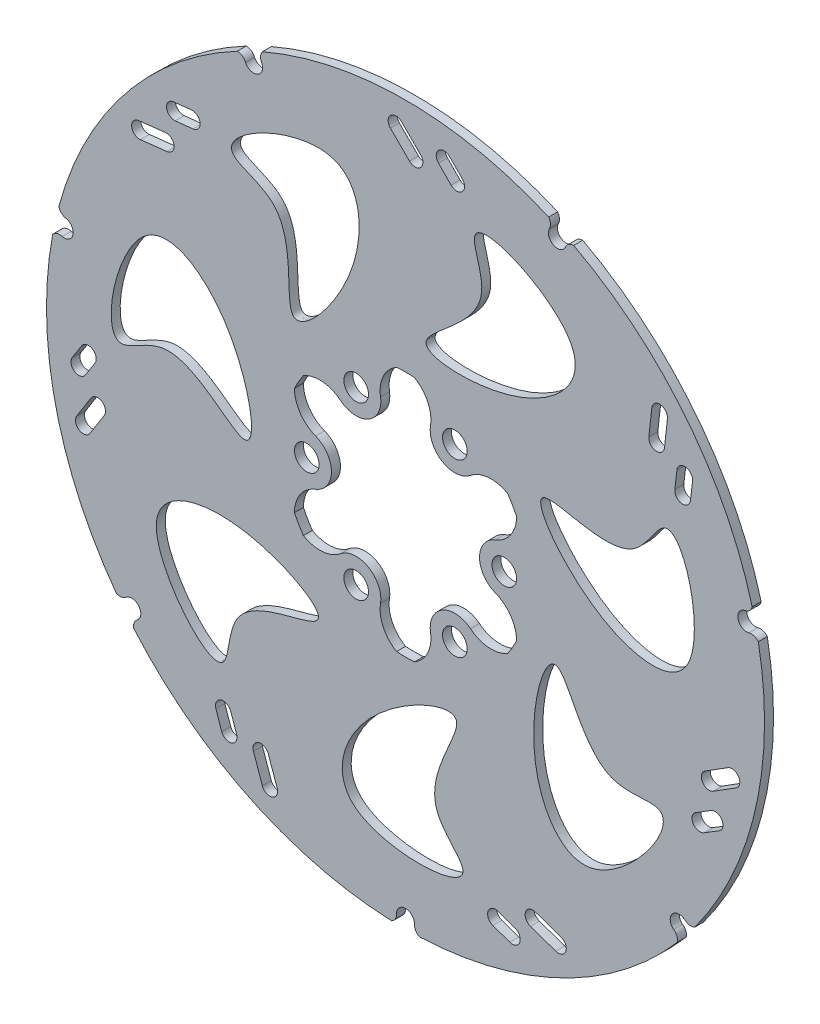
SolidWorks part; units mm, degrees
ref_plane "Płaszczyzna przednia" through (0, 0, 0) normal (0, 0, 1) x (1, 0, 0)
ref_plane "Płaszczyzna górna" through (0, 0, 0) normal (0, 1, 0) x (1, 0, 0)
ref_plane "Płaszczyzna prawa" through (0, 0, 0) normal (1, 0, 0) x (0, 0, -1)
sketch "Szkic1" plane through (0, 0, 0) normal (0, 0, 1) x (1, 0, 0)
  line L0 (0, 100.2963) -> (0, -100.5622) construction
  line L1 (96.5218, 0) -> (-95.8606, 0) construction
  line L2 (0, 72) -> (-5.2968, 77.2968) construction
  line L3 (0, 72) -> (7.8433, 64.1567) construction
  line L4 (-2.1213, 74.1213) -> (2.1213, 69.8787) construction
  line L5 (-0.8839, 75.3588) -> (3.3588, 71.1161)
  line L6 (-3.3588, 72.8839) -> (0.8839, 68.6412)
  line L7 (10, 71.3022) -> (13.4645, 67.8377) construction
  line L8 (10, 71.3022) -> (6.4186, 74.9311) construction
  line L9 (8.5951, 72.7257) -> (11.4049, 69.8787) construction
  line L10 (9.8407, 73.9549) -> (12.6504, 71.1079)
  line L11 (7.3496, 71.4964) -> (10.1593, 68.6494)
  line L12 (54.8888, 48.0683) -> (54.217, 42.1061)
  line L13 (14.2339, 69.8787) -> (-2.5812, 69.8787) construction
  line L14 (58.3668, 47.6765) -> (57.695, 41.7142)
  line L15 (60.4805, 38.8312) -> (60.0065, 34.8593)
  line L16 (63.9559, 38.4164) -> (63.4818, 34.4446)
  line L17 (56.6278, 47.8724) -> (55.956, 41.9101) construction
  line L18 (62.2182, 38.6238) -> (61.7442, 34.652) construction
  line L19 (71.8039, -12.9436) -> (66.7236, -16.1358)
  line L20 (73.666, -15.9072) -> (68.5857, -19.0994)
  line L21 (68.0684, -23.0747) -> (64.6676, -25.1805)
  line L22 (69.911, -26.0505) -> (66.5101, -28.1563)
  line L23 (72.735, -14.4254) -> (67.6546, -17.6176) construction
  line L24 (68.9897, -24.5626) -> (65.5889, -26.6684) construction
  line L25 (34.6493, -64.2088) -> (28.986, -62.2271)
  line L26 (33.4933, -67.5124) -> (27.83, -65.5307)
  line L27 (24.3994, -67.6049) -> (20.6326, -66.2589)
  line L28 (23.2217, -70.9008) -> (19.4549, -69.5549)
  line L29 (34.0713, -65.8606) -> (28.408, -63.8789) construction
  line L30 (23.8105, -69.2528) -> (20.0438, -67.9069) construction
  line L31 (-28.597, -67.1234) -> (-30.5787, -61.4601)
  line L32 (-31.9006, -68.2794) -> (-33.8823, -62.6161)
  line L33 (-37.6429, -61.2272) -> (-38.9391, -57.443)
  line L34 (-40.954, -62.3614) -> (-42.2502, -58.5772)
  line L35 (-30.2488, -67.7014) -> (-32.2305, -62.0381) construction
  line L36 (-39.2984, -61.7943) -> (-40.5947, -58.0101) construction
  line L37 (-70.3091, -19.4927) -> (-67.1169, -14.4124)
  line L38 (-73.2727, -17.6306) -> (-70.0805, -12.5503)
  line L39 (-71.3393, -8.7441) -> (-69.1889, -5.3713)
  line L40 (-74.2905, -6.8626) -> (-72.1401, -3.4897)
  line L41 (-71.7909, -18.5617) -> (-68.5987, -13.4813) construction
  line L42 (-72.8149, -7.8034) -> (-70.6645, -4.4305) construction
  line L43 (-59.0771, 42.8164) -> (-53.1148, 43.4882)
  line L44 (-59.4689, 46.2944) -> (-53.5067, 46.9662)
  line L45 (-51.3158, 50.3234) -> (-47.338, 50.7451)
  line L46 (-51.6847, 53.8039) -> (-47.707, 54.2256)
  line L47 (-59.273, 44.5554) -> (-53.3107, 45.2272) construction
  line L48 (-51.5002, 52.0637) -> (-47.5225, 52.4853) construction
  line L49 (0, 0) -> (0.8839, 68.6412) construction
  line L50 (-7.2215, -78) -> (6.4186, -78) construction
  line L51 (0, 0) -> (0, -78) construction
  line L52 (24.75, 11.987) -> (24.75, 17.3566) construction
  line L53 (24.75, -11.987) -> (24.75, -17.6176) construction
  line L54 (10.5123, -30.9016) -> (-11.2813, -62.0261) construction
  circle A0 centre (0, 0) radius 80
  circle A1 centre (0, 0) radius 22 construction
  circle A2 centre (0, 0) radius 72 construction
  circle A3 centre (0, 0) radius 16.5
  arc A4 (-0.8839, 75.3588) -> (-3.3588, 72.8839) centre (-2.1213, 74.1213) ccw
  arc A5 (0.8839, 68.6412) -> (3.3588, 71.1161) centre (2.1213, 69.8787) ccw
  arc A6 (9.8407, 73.9549) -> (7.3496, 71.4964) centre (8.5951, 72.7257) ccw
  arc A7 (10.1593, 68.6494) -> (12.6504, 71.1079) centre (11.4049, 69.8787) ccw
  arc A8 (58.3668, 47.6765) -> (54.8888, 48.0683) centre (56.6278, 47.8724) ccw
  arc A9 (54.217, 42.1061) -> (57.695, 41.7142) centre (55.956, 41.9101) ccw
  arc A10 (63.9559, 38.4164) -> (60.4805, 38.8312) centre (62.2182, 38.6238) ccw
  arc A11 (60.0065, 34.8593) -> (63.4818, 34.4446) centre (61.7442, 34.652) ccw
  arc A12 (73.666, -15.9072) -> (71.8039, -12.9436) centre (72.735, -14.4254) ccw
  arc A13 (66.7236, -16.1358) -> (68.5857, -19.0994) centre (67.6546, -17.6176) ccw
  arc A14 (69.911, -26.0505) -> (68.0684, -23.0747) centre (68.9897, -24.5626) ccw
  arc A15 (64.6676, -25.1805) -> (66.5101, -28.1563) centre (65.5889, -26.6684) ccw
  arc A16 (33.4933, -67.5124) -> (34.6493, -64.2088) centre (34.0713, -65.8606) ccw
  arc A17 (28.986, -62.2271) -> (27.83, -65.5307) centre (28.408, -63.8789) ccw
  arc A18 (23.2217, -70.9008) -> (24.3994, -67.6049) centre (23.8105, -69.2528) ccw
  arc A19 (20.6326, -66.2589) -> (19.4549, -69.5549) centre (20.0438, -67.9069) ccw
  arc A20 (-31.9006, -68.2794) -> (-28.597, -67.1234) centre (-30.2488, -67.7014) ccw
  arc A21 (-30.5787, -61.4601) -> (-33.8823, -62.6161) centre (-32.2305, -62.0381) ccw
  arc A22 (-40.954, -62.3614) -> (-37.6429, -61.2272) centre (-39.2984, -61.7943) ccw
  arc A23 (-38.9391, -57.443) -> (-42.2502, -58.5772) centre (-40.5947, -58.0101) ccw
  arc A24 (-73.2727, -17.6306) -> (-70.3091, -19.4927) centre (-71.7909, -18.5617) ccw
  arc A25 (-67.1169, -14.4124) -> (-70.0805, -12.5503) centre (-68.5987, -13.4813) ccw
  arc A26 (-74.2905, -6.8626) -> (-71.3393, -8.7441) centre (-72.8149, -7.8034) ccw
  arc A27 (-69.1889, -5.3713) -> (-72.1401, -3.4897) centre (-70.6645, -4.4305) ccw
  arc A28 (-59.4689, 46.2944) -> (-59.0771, 42.8164) centre (-59.273, 44.5554) ccw
  arc A29 (-53.1148, 43.4882) -> (-53.5067, 46.9662) centre (-53.3107, 45.2272) ccw
  arc A30 (-51.6847, 53.8039) -> (-51.3158, 50.3234) centre (-51.5002, 52.0637) ccw
  arc A31 (-47.338, 50.7451) -> (-47.707, 54.2256) centre (-47.5225, 52.4853) ccw
  circle A32 centre (0, -78) radius 2 construction
  arc A33 (-2, -78) -> (2, -78) centre (0, -78) cw
  arc A34 (2, -78) -> (3.0983, -79.94) centre (3.9942, -78.1519) ccw
  arc A35 (-2, -78) -> (-3.0983, -79.94) centre (-3.9942, -78.1519) cw
  arc A36 (-59.7359, -50.1959) -> (-60.5679, -52.2641) centre (-58.6113, -51.8497) ccw
  arc A37 (-62.2298, -47.0685) -> (-59.7359, -50.1959) centre (-60.9829, -48.6322) cw
  arc A38 (-62.2298, -47.0685) -> (-64.4313, -47.4195) centre (-63.592, -45.6041) cw
  arc A39 (-76.4894, 15.4068) -> (-78.6251, 14.7677) centre (-77.0813, 13.4964) ccw
  arc A40 (-75.5993, 19.3065) -> (-76.4894, 15.4068) centre (-76.0444, 17.3566) cw
  arc A41 (-75.5993, 19.3065) -> (-77.2463, 20.8089) centre (-75.3037, 21.2845) cw
  arc A42 (-35.6449, 69.4078) -> (-37.4761, 70.6792) centre (-37.5075, 68.6794) ccw
  arc A43 (-32.041, 71.1433) -> (-35.6449, 69.4078) centre (-33.8429, 70.2756) cw
  arc A44 (-32.041, 71.1433) -> (-31.8932, 73.3677) centre (-30.3102, 72.1455) cw
  arc A45 (32.041, 71.1433) -> (31.8932, 73.3677) centre (30.3102, 72.1455) ccw
  arc A46 (35.6449, 69.4078) -> (32.041, 71.1433) centre (33.8429, 70.2756) cw
  arc A47 (35.6449, 69.4078) -> (37.4761, 70.6792) centre (37.5075, 68.6794) cw
  arc A48 (75.5993, 19.3065) -> (77.2463, 20.8089) centre (75.3037, 21.2845) ccw
  arc A49 (76.4894, 15.4068) -> (75.5993, 19.3065) centre (76.0444, 17.3566) cw
  arc A50 (76.4894, 15.4068) -> (78.6251, 14.7677) centre (77.0813, 13.4964) cw
  arc A51 (62.2298, -47.0685) -> (64.4313, -47.4195) centre (63.592, -45.6041) ccw
  arc A52 (59.7359, -50.1959) -> (62.2298, -47.0685) centre (60.9829, -48.6322) cw
  arc A53 (59.7359, -50.1959) -> (60.5679, -52.2641) centre (58.6113, -51.8497) cw
  circle A54 centre (0, 0) radius 78 construction
  circle A55 centre (22, 0) radius 2.75
  circle A56 centre (11, -19.0526) radius 2.75
  circle A57 centre (-11, -19.0526) radius 2.75
  circle A58 centre (-22, 0) radius 2.75
  circle A59 centre (-11, 19.0526) radius 2.75
  circle A60 centre (11, 19.0526) radius 2.75
  circle A61 centre (22, 0) radius 5.5 construction
  arc A62 (20.0357, -5.1373) -> (20.0357, 5.1373) centre (22, 0) cw
  arc A63 (24.75, -11.987) -> (20.0357, -5.1373) centre (17.4167, -11.987) ccw
  circle A64 centre (0, 0) radius 27.5 construction
  arc A65 (24.75, 11.987) -> (20.0357, 5.1373) centre (17.4167, 11.987) cw
  arc A66 (24.75, -11.987) -> (24.75, 11.987) centre (0, 0) ccw
  arc A67 (22.756, -15.4406) -> (14.4669, -14.7828) centre (19.0894, -9.0898) cw
  arc A68 (5.5688, -19.9201) -> (14.4669, -14.7828) centre (11, -19.0526) cw
  arc A69 (1.994, -27.4276) -> (5.5688, -19.9201) centre (-1.6727, -21.0768) ccw
  arc A70 (1.994, -27.4276) -> (22.756, -15.4406) centre (0, 0) ccw
  arc A71 (-1.994, -27.4276) -> (-5.5688, -19.9201) centre (1.6727, -21.0768) cw
  arc A72 (-14.4669, -14.7828) -> (-5.5688, -19.9201) centre (-11, -19.0526) cw
  arc A73 (-22.756, -15.4406) -> (-14.4669, -14.7828) centre (-19.0894, -9.0898) ccw
  arc A74 (-22.756, -15.4406) -> (-1.994, -27.4276) centre (0, 0) ccw
  arc A75 (-24.75, -11.987) -> (-20.0357, -5.1373) centre (-17.4167, -11.987) cw
  arc A76 (-20.0357, 5.1373) -> (-20.0357, -5.1373) centre (-22, 0) cw
  arc A77 (-24.75, 11.987) -> (-20.0357, 5.1373) centre (-17.4167, 11.987) ccw
  arc A78 (-24.75, 11.987) -> (-24.75, -11.987) centre (0, 0) ccw
  arc A79 (-22.756, 15.4406) -> (-14.4669, 14.7828) centre (-19.0894, 9.0898) cw
  arc A80 (-5.5688, 19.9201) -> (-14.4669, 14.7828) centre (-11, 19.0526) cw
  arc A81 (-1.994, 27.4276) -> (-5.5688, 19.9201) centre (1.6727, 21.0768) ccw
  arc A82 (-1.994, 27.4276) -> (-22.756, 15.4406) centre (0, 0) ccw
  arc A83 (1.994, 27.4276) -> (5.5688, 19.9201) centre (-1.6727, 21.0768) cw
  arc A84 (14.4669, 14.7828) -> (5.5688, 19.9201) centre (11, 19.0526) cw
  arc A85 (22.756, 15.4406) -> (14.4669, 14.7828) centre (19.0894, 9.0898) ccw
  arc A86 (22.756, 15.4406) -> (1.994, 27.4276) centre (0, 0) ccw
  arc A87 (22.756, 15.4406) -> (24.75, 11.987) centre (0, 0) cw
  arc A88 (1.994, -27.4276) -> (22.756, -15.4406) centre (0, 0) ccw
  arc A89 (1.994, -27.4276) -> (5.5688, -19.9201) centre (-1.6727, -21.0768) ccw
  arc A90 (5.5688, -19.9201) -> (14.4669, -14.7828) centre (11, -19.0526) cw
  arc A91 (22.756, -15.4406) -> (14.4669, -14.7828) centre (19.0894, -9.0898) cw
  arc A92 (24.75, -11.987) -> (22.756, -15.4406) centre (0, 0) cw
  arc A93 (-22.756, -15.4406) -> (-1.994, -27.4276) centre (0, 0) ccw
  arc A94 (-22.756, -15.4406) -> (-14.4669, -14.7828) centre (-19.0894, -9.0898) ccw
  arc A95 (-14.4669, -14.7828) -> (-5.5688, -19.9201) centre (-11, -19.0526) cw
  arc A96 (-1.994, -27.4276) -> (-5.5688, -19.9201) centre (1.6727, -21.0768) cw
  arc A97 (1.994, -27.4276) -> (-1.994, -27.4276) centre (0, 0) cw
  arc A98 (-24.75, 11.987) -> (-24.75, -11.987) centre (0, 0) ccw
  arc A99 (-24.75, 11.987) -> (-20.0357, 5.1373) centre (-17.4167, 11.987) ccw
  arc A100 (-20.0357, 5.1373) -> (-20.0357, -5.1373) centre (-22, 0) cw
  arc A101 (-24.75, -11.987) -> (-20.0357, -5.1373) centre (-17.4167, -11.987) cw
  arc A102 (-22.756, -15.4406) -> (-24.75, -11.987) centre (0, 0) cw
  arc A103 (-1.994, 27.4276) -> (-22.756, 15.4406) centre (0, 0) ccw
  arc A104 (-1.994, 27.4276) -> (-5.5688, 19.9201) centre (1.6727, 21.0768) ccw
  arc A105 (-5.5688, 19.9201) -> (-14.4669, 14.7828) centre (-11, 19.0526) cw
  arc A106 (-22.756, 15.4406) -> (-14.4669, 14.7828) centre (-19.0894, 9.0898) cw
  arc A107 (-24.75, 11.987) -> (-22.756, 15.4406) centre (0, 0) cw
  arc A108 (22.756, 15.4406) -> (1.994, 27.4276) centre (0, 0) ccw
  arc A109 (22.756, 15.4406) -> (14.4669, 14.7828) centre (19.0894, 9.0898) ccw
  arc A110 (14.4669, 14.7828) -> (5.5688, 19.9201) centre (11, 19.0526) cw
  arc A111 (1.994, 27.4276) -> (5.5688, 19.9201) centre (-1.6727, 21.0768) cw
  arc A112 (-1.994, 27.4276) -> (1.994, 27.4276) centre (0, 0) cw
  circle A114 centre (7, -62) radius 5.75 construction
  ellipse E1 centre (0, -48) end of major axis (-11.2813, -62.0261) minor radius 9 construction
  spline S0 degree 2 poles (-3.0983, -79.94) (0, -80.06) (3.0983, -79.94) knots 0 0 0 1 1 1
  spline S1 degree 2 poles (-64.4313, -47.4195) (-62.5934, -49.9166) (-60.5679, -52.2641) knots 0 0 0 1 1 1
  spline S2 degree 2 poles (-77.2463, 20.8089) (-78.0527, 17.815) (-78.6251, 14.7677) knots 0 0 0 1 1 1
  spline S3 degree 2 poles (-31.8932, 73.3677) (-34.7367, 72.1316) (-37.4761, 70.6792) knots 0 0 0 1 1 1
  spline S4 degree 2 poles (37.4761, 70.6792) (34.7367, 72.1316) (31.8932, 73.3677) knots 0 0 0 1 1 1
  spline S5 degree 2 poles (78.6251, 14.7677) (78.0527, 17.815) (77.2463, 20.8089) knots 0 0 0 1 1 1
  spline S6 degree 2 poles (60.5679, -52.2641) (62.5934, -49.9166) (64.4313, -47.4195) knots 0 0 0 1 1 1
  spline S7 degree 3 poles (-20.3501, -67.8385) (21.7118, -66.5845) (0.4085, -51.6335) (20.4901, -26.7411) (-10.7012, -40.3123) (-20.3501, -67.8385) (21.7118, -66.5845) (0.4085, -51.6335) knots -0.679903 -0.467042 -0.254182 0 0.107237 0.320097 0.532958 0.745818 1 1.107237 1.320097 1.532958 only from (12.75, -62) to (12.75, -62)
  spline S8 degree 3 poles (-65.7264, -26.3863) (-38.5208, -58.4898) (-40.114, -32.5123) (-8.1316, -32.6926) (-38.1895, -16.7678) (-65.7264, -26.3863) (-38.5208, -58.4898) (-40.114, -32.5123) knots -0.679903 -0.467042 -0.254182 0 0.107237 0.320097 0.532958 0.745818 1 1.107237 1.320097 1.532958 only from (-40.5241, -48.6247) to (-40.5241, -48.6247)
  spline S9 degree 3 poles (-61.6093, 34.9354) (-69.7465, -6.351) (-50.4298, 11.0913) (-30.6301, -14.0259) (-36.9204, 19.4032) (-61.6093, 34.9354) (-69.7465, -6.351) (-50.4298, 11.0913) knots -0.679903 -0.467042 -0.254182 0 0.107237 0.320097 0.532958 0.745818 1 1.107237 1.320097 1.532958 only from (-63.2827, 1.366) to (-63.2827, 1.366)
  spline S10 degree 3 poles (-11.0992, 69.95) (-48.4516, 50.5702) (-22.771, 46.3429) (-30.0635, 15.2025) (-7.8494, 40.9632) (-11.0992, 69.95) (-48.4516, 50.5702) (-22.771, 46.3429) knots -0.679903 -0.467042 -0.254182 0 0.107237 0.320097 0.532958 0.745818 1 1.107237 1.320097 1.532958 only from (-38.3881, 50.3281) to (-38.3881, 50.3281)
  spline S11 degree 3 poles (47.7688, 52.2908) (9.3283, 69.411) (22.0349, 46.6974) (-6.8584, 32.9832) (27.1323, 31.6771) (47.7688, 52.2908) (9.3283, 69.411) (22.0349, 46.6974) knots -0.679903 -0.467042 -0.254182 0 0.107237 0.320097 0.532958 0.745818 1 1.107237 1.320097 1.532958 only from (15.4134, 61.3921) to (15.4134, 61.3921)
  spline S12 degree 3 poles (70.666, -4.7444) (60.0838, 35.9839) (50.248, 11.8878) (21.5111, 25.9268) (41.6829, -1.4626) (70.666, -4.7444) (60.0838, 35.9839) (50.248, 11.8878) knots -0.679903 -0.467042 -0.254182 0 0.107237 0.320097 0.532958 0.745818 1 1.107237 1.320097 1.532958 only from (57.6084, 26.2266) to (57.6084, 26.2266)
  spline S13 degree 3 poles (40.3502, -58.207) (65.595, -24.5398) (40.6234, -31.8736) (33.6824, -0.653) (24.8454, -33.5009) (40.3502, -58.207) (65.595, -24.5398) (40.6234, -31.8736) knots -0.679903 -0.467042 -0.254182 0 0.107237 0.320097 0.532958 0.745818 1 1.107237 1.320097 1.532958 only from (56.423, -28.688) to (56.423, -28.688)
  point P15 (0, 72)
  point P20 (10, 71.3022)
  point P26 (10, 71.3022)
  point P37 (56.2919, 44.8913)
  point P44 (61.9812, 36.6379)
  point P51 (70.1948, -16.0215)
  point P58 (67.2893, -25.6155)
  point P65 (31.2396, -64.8698)
  point P72 (21.9272, -68.5799)
  point P79 (-31.2396, -64.8698)
  point P86 (-39.9465, -59.9022)
  point P93 (-70.1948, -16.0215)
  point P100 (-71.7397, -6.1169)
  point P107 (-56.2919, 44.8913)
  point P114 (-49.5114, 52.2745)
  point P195 (0, 0)
  point P198 (24.75, 11.987)
  point P203 (24.75, -11.987)
  point P250 (0, 0)
  point P292 (0, 0)
  point P336 (0, 0)
  dimension "D1" = 160
  dimension "D2" = 33
  dimension "D3" = 44
  dimension "D4" = 144
  dimension "D16" = 156
  dimension "D17" = 4
  dimension "D18" = 2
  dimension "D19" = 0.1519
  dimension "D22" = 5.5
  dimension "D24" = 5.5
  dimension "D25" = 6
  dimension "D28" = 62
  dimension "D29" = 11.5
  dimension "D34" = 22
  dimension "D5" = 6
  dimension "D6" = 3.5
  dimension "D7" = 10
  dimension "D8" = 3.5
  dimension "D9" = 4
  dimension "D10" = 45
  dimension "D11" = 45
  dimension "D12" = 90
  dimension "D14" = 68.6469
  dimension "D15" = 0.738
  dimension "D20" = 0.1519
  dimension "D26" = 0
  dimension "D27" = 48
  dimension "D30" = 7
  dimension "D31" = 18
  dimension "D32" = 18
  dimension "D33" = 35
  dimension "D35" = 0
  dimension "D13" = 7
  dimension "D21" = 7
  dimension "D23" = 6
extrude "Dodanie-wyciągnięcie1" add sketch "Szkic1" along normal blind 2 contours A53 A52 A51 A0 A50 A49 A48 A47 A46 A45 A44 A43 A42 A41 A40 A39 A38 A37 A36 A35 A33 A34 S13 S12 S11 S10 S9 S8 S7 A31 L45 A30 L46 A29 L43 A28 | A69 A70 A67 A68 A56 | A63 A66 A65 A62 A55 | A85 A86 A83 A84 A60 | A81 A82 A79 A80 A59 | A77 A78 A75 A76 A58 | A73 A74 A71 A72 A57
